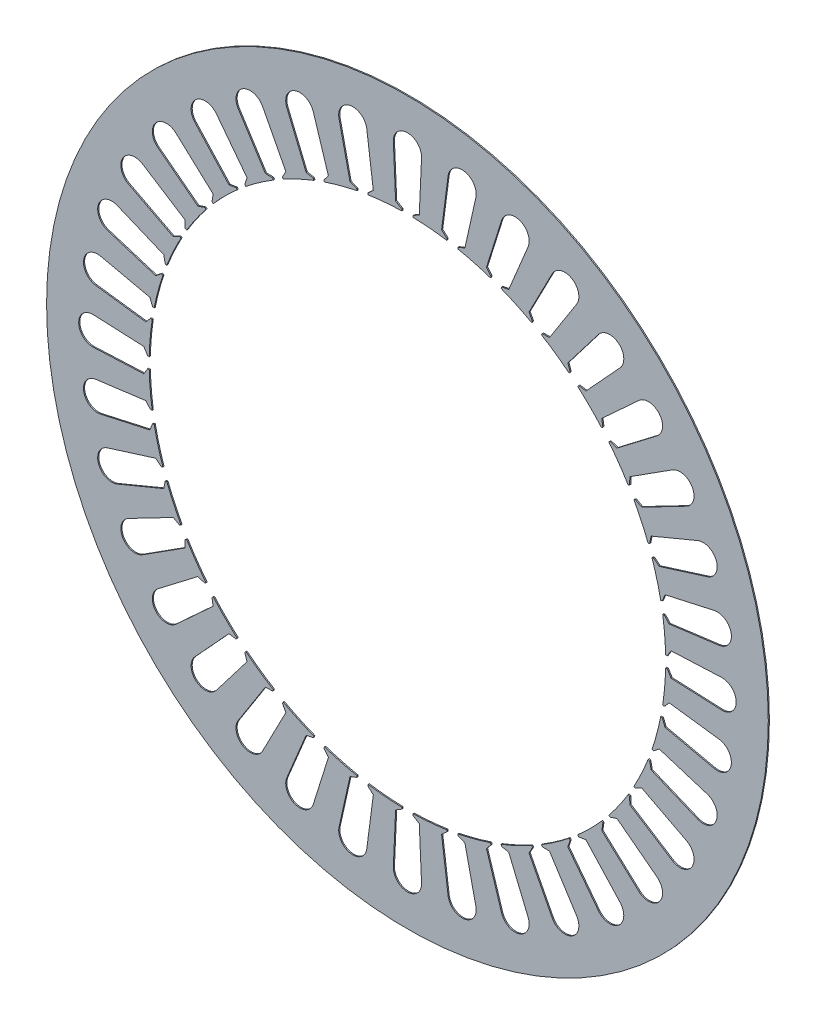
SolidWorks part; units mm, degrees
material "M19 Silicon Steel (29 Gauge)"
ref_plane "Front Plane" through (0, 0, 0) normal (0, 0, 1) x (1, 0, 0)
ref_plane "Top Plane" through (0, 0, 0) normal (0, 1, 0) x (1, 0, 0)
ref_plane "Right Plane" through (0, 0, 0) normal (1, 0, 0) x (0, 0, -1)
sketch "Stator sketch" plane through (0, 0, 0) normal (0, 0, 1) x (1, 0, 0)
  line L0 (0, 0) -> (0, 64) construction
  line L1 (2.0989, 46.7539) -> (2.5, 55.6878)
  line L2 (-2.0989, 46.7539) -> (-2.5, 55.6878)
  line L5 (-1.0066, 46.0891) -> (-2.0989, 46.7539)
  line L6 (-1, 45.7891) -> (-1.0066, 46.0891)
  line L7 (1.0066, 46.0891) -> (2.0989, 46.7539)
  line L8 (1, 45.7891) -> (1.0066, 46.0891)
  line L9 (6.9664, 45.2671) -> (7.012, 45.5637)
  line L10 (7.012, 45.5637) -> (6.0517, 46.4081)
  line L11 (6.0517, 46.4081) -> (7.2081, 55.2759)
  line L12 (8.936, 44.9198) -> (8.9945, 45.2141)
  line L13 (8.9945, 45.2141) -> (10.1858, 45.6791)
  line L14 (10.1858, 45.6791) -> (12.1321, 54.4076)
  line L15 (14.7211, 43.3697) -> (14.8175, 43.6538)
  line L16 (14.8175, 43.6538) -> (14.0184, 44.6522)
  line L17 (14.0184, 44.6522) -> (16.6971, 53.1844)
  line L18 (16.6005, 42.6856) -> (16.7092, 42.9653)
  line L19 (16.7092, 42.9653) -> (17.9631, 43.2164)
  line L20 (17.9631, 43.2164) -> (21.3956, 51.4743)
  line L21 (22.0285, 40.1545) -> (22.1728, 40.4176)
  line L22 (22.1728, 40.4176) -> (21.5592, 41.5395)
  line L23 (21.5592, 41.5395) -> (25.6788, 49.477)
  line L24 (23.7606, 39.1545) -> (23.9162, 39.411)
  line L25 (23.9162, 39.411) -> (25.1947, 39.4406)
  line L26 (25.1947, 39.4406) -> (30.0089, 46.977)
  line L27 (28.6666, 35.7193) -> (28.8544, 35.9533)
  line L28 (28.8544, 35.9533) -> (28.445, 37.1647)
  line L29 (28.445, 37.1647) -> (33.8803, 44.2663)
  line L30 (30.1987, 34.4337) -> (30.3966, 34.6593)
  line L31 (30.3966, 34.6593) -> (31.6607, 34.4664)
  line L32 (31.6607, 34.4664) -> (37.7105, 41.0523)
  line L33 (34.4337, 30.1987) -> (34.6593, 30.3966)
  line L34 (34.6593, 30.3966) -> (34.4664, 31.6607)
  line L35 (34.4664, 31.6607) -> (41.0523, 37.7105)
  line L36 (35.7193, 28.6666) -> (35.9533, 28.8544)
  line L37 (35.9533, 28.8544) -> (37.1647, 28.445)
  line L38 (37.1647, 28.445) -> (44.2663, 33.8803)
  line L39 (39.1545, 23.7606) -> (39.411, 23.9162)
  line L40 (39.411, 23.9162) -> (39.4406, 25.1947)
  line L41 (39.4406, 25.1947) -> (46.977, 30.0089)
  line L42 (40.1545, 22.0285) -> (40.4176, 22.1728)
  line L43 (40.4176, 22.1728) -> (41.5395, 21.5592)
  line L44 (41.5395, 21.5592) -> (49.477, 25.6788)
  line L45 (42.6856, 16.6005) -> (42.9653, 16.7092)
  line L46 (42.9653, 16.7092) -> (43.2164, 17.9631)
  line L47 (43.2164, 17.9631) -> (51.4743, 21.3956)
  line L48 (43.3697, 14.7211) -> (43.6538, 14.8175)
  line L49 (43.6538, 14.8175) -> (44.6522, 14.0184)
  line L50 (44.6522, 14.0184) -> (53.1844, 16.6971)
  line L51 (44.9198, 8.936) -> (45.2141, 8.9945)
  line L52 (45.2141, 8.9945) -> (45.6791, 10.1858)
  line L53 (45.6791, 10.1858) -> (54.4076, 12.1321)
  line L54 (45.2671, 6.9664) -> (45.5637, 7.012)
  line L55 (45.5637, 7.012) -> (46.4081, 6.0517)
  line L56 (46.4081, 6.0517) -> (55.2759, 7.2081)
  line L57 (45.7891, 1) -> (46.0891, 1.0066)
  line L58 (46.0891, 1.0066) -> (46.7539, 2.0989)
  line L59 (46.7539, 2.0989) -> (55.6878, 2.5)
  line L60 (45.7891, -1) -> (46.0891, -1.0066)
  line L61 (46.0891, -1.0066) -> (46.7539, -2.0989)
  line L62 (46.7539, -2.0989) -> (55.6878, -2.5)
  line L63 (45.2671, -6.9664) -> (45.5637, -7.012)
  line L64 (45.5637, -7.012) -> (46.4081, -6.0517)
  line L65 (46.4081, -6.0517) -> (55.2759, -7.2081)
  line L66 (44.9198, -8.936) -> (45.2141, -8.9945)
  line L67 (45.2141, -8.9945) -> (45.6791, -10.1858)
  line L68 (45.6791, -10.1858) -> (54.4076, -12.1321)
  line L69 (43.3697, -14.7211) -> (43.6538, -14.8175)
  line L70 (43.6538, -14.8175) -> (44.6522, -14.0184)
  line L71 (44.6522, -14.0184) -> (53.1844, -16.6971)
  line L72 (42.6856, -16.6005) -> (42.9653, -16.7092)
  line L73 (42.9653, -16.7092) -> (43.2164, -17.9631)
  line L74 (43.2164, -17.9631) -> (51.4743, -21.3956)
  line L75 (40.1545, -22.0285) -> (40.4176, -22.1728)
  line L76 (40.4176, -22.1728) -> (41.5395, -21.5592)
  line L77 (41.5395, -21.5592) -> (49.477, -25.6788)
  line L78 (39.1545, -23.7606) -> (39.411, -23.9162)
  line L79 (39.411, -23.9162) -> (39.4406, -25.1947)
  line L80 (39.4406, -25.1947) -> (46.977, -30.0089)
  line L81 (35.7193, -28.6666) -> (35.9533, -28.8544)
  line L82 (35.9533, -28.8544) -> (37.1647, -28.445)
  line L83 (37.1647, -28.445) -> (44.2663, -33.8803)
  line L84 (34.4337, -30.1987) -> (34.6593, -30.3966)
  line L85 (34.6593, -30.3966) -> (34.4664, -31.6607)
  line L86 (34.4664, -31.6607) -> (41.0523, -37.7105)
  line L87 (30.1987, -34.4337) -> (30.3966, -34.6593)
  line L88 (30.3966, -34.6593) -> (31.6607, -34.4664)
  line L89 (31.6607, -34.4664) -> (37.7105, -41.0523)
  line L90 (28.6666, -35.7193) -> (28.8544, -35.9533)
  line L91 (28.8544, -35.9533) -> (28.445, -37.1647)
  line L92 (28.445, -37.1647) -> (33.8803, -44.2663)
  line L93 (23.7606, -39.1545) -> (23.9162, -39.411)
  line L94 (23.9162, -39.411) -> (25.1947, -39.4406)
  line L95 (25.1947, -39.4406) -> (30.0089, -46.977)
  line L96 (22.0285, -40.1545) -> (22.1728, -40.4176)
  line L97 (22.1728, -40.4176) -> (21.5592, -41.5395)
  line L98 (21.5592, -41.5395) -> (25.6788, -49.477)
  line L99 (16.6005, -42.6856) -> (16.7092, -42.9653)
  line L100 (16.7092, -42.9653) -> (17.9631, -43.2164)
  line L101 (17.9631, -43.2164) -> (21.3956, -51.4743)
  line L102 (14.7211, -43.3697) -> (14.8175, -43.6538)
  line L103 (14.8175, -43.6538) -> (14.0184, -44.6522)
  line L104 (14.0184, -44.6522) -> (16.6971, -53.1844)
  line L105 (8.936, -44.9198) -> (8.9945, -45.2141)
  line L106 (8.9945, -45.2141) -> (10.1858, -45.6791)
  line L107 (10.1858, -45.6791) -> (12.1321, -54.4076)
  line L108 (6.9664, -45.2671) -> (7.012, -45.5637)
  line L109 (7.012, -45.5637) -> (6.0517, -46.4081)
  line L110 (6.0517, -46.4081) -> (7.2081, -55.2759)
  line L111 (1, -45.7891) -> (1.0066, -46.0891)
  line L112 (1.0066, -46.0891) -> (2.0989, -46.7539)
  line L113 (2.0989, -46.7539) -> (2.5, -55.6878)
  line L114 (-1, -45.7891) -> (-1.0066, -46.0891)
  line L115 (-1.0066, -46.0891) -> (-2.0989, -46.7539)
  line L116 (-2.0989, -46.7539) -> (-2.5, -55.6878)
  line L117 (-6.9664, -45.2671) -> (-7.012, -45.5637)
  line L118 (-7.012, -45.5637) -> (-6.0517, -46.4081)
  line L119 (-6.0517, -46.4081) -> (-7.2081, -55.2759)
  line L120 (-8.936, -44.9198) -> (-8.9945, -45.2141)
  line L121 (-8.9945, -45.2141) -> (-10.1858, -45.6791)
  line L122 (-10.1858, -45.6791) -> (-12.1321, -54.4076)
  line L123 (-14.7211, -43.3697) -> (-14.8175, -43.6538)
  line L124 (-14.8175, -43.6538) -> (-14.0184, -44.6522)
  line L125 (-14.0184, -44.6522) -> (-16.6971, -53.1844)
  line L126 (-16.6005, -42.6856) -> (-16.7092, -42.9653)
  line L127 (-16.7092, -42.9653) -> (-17.9631, -43.2164)
  line L128 (-17.9631, -43.2164) -> (-21.3956, -51.4743)
  line L129 (-22.0285, -40.1545) -> (-22.1728, -40.4176)
  line L130 (-22.1728, -40.4176) -> (-21.5592, -41.5395)
  line L131 (-21.5592, -41.5395) -> (-25.6788, -49.477)
  line L132 (-23.7606, -39.1545) -> (-23.9162, -39.411)
  line L133 (-23.9162, -39.411) -> (-25.1947, -39.4406)
  line L134 (-25.1947, -39.4406) -> (-30.0089, -46.977)
  line L135 (-28.6666, -35.7193) -> (-28.8544, -35.9533)
  line L136 (-28.8544, -35.9533) -> (-28.445, -37.1647)
  line L137 (-28.445, -37.1647) -> (-33.8803, -44.2663)
  line L138 (-30.1987, -34.4337) -> (-30.3966, -34.6593)
  line L139 (-30.3966, -34.6593) -> (-31.6607, -34.4664)
  line L140 (-31.6607, -34.4664) -> (-37.7105, -41.0523)
  line L141 (-34.4337, -30.1987) -> (-34.6593, -30.3966)
  line L142 (-34.6593, -30.3966) -> (-34.4664, -31.6607)
  line L143 (-34.4664, -31.6607) -> (-41.0523, -37.7105)
  line L144 (-35.7193, -28.6666) -> (-35.9533, -28.8544)
  line L145 (-35.9533, -28.8544) -> (-37.1647, -28.445)
  line L146 (-37.1647, -28.445) -> (-44.2663, -33.8803)
  line L147 (-39.1545, -23.7606) -> (-39.411, -23.9162)
  line L148 (-39.411, -23.9162) -> (-39.4406, -25.1947)
  line L149 (-39.4406, -25.1947) -> (-46.977, -30.0089)
  line L150 (-40.1545, -22.0285) -> (-40.4176, -22.1728)
  line L151 (-40.4176, -22.1728) -> (-41.5395, -21.5592)
  line L152 (-41.5395, -21.5592) -> (-49.477, -25.6788)
  line L153 (-42.6856, -16.6005) -> (-42.9653, -16.7092)
  line L154 (-42.9653, -16.7092) -> (-43.2164, -17.9631)
  line L155 (-43.2164, -17.9631) -> (-51.4743, -21.3956)
  line L156 (-43.3697, -14.7211) -> (-43.6538, -14.8175)
  line L157 (-43.6538, -14.8175) -> (-44.6522, -14.0184)
  line L158 (-44.6522, -14.0184) -> (-53.1844, -16.6971)
  line L159 (-44.9198, -8.936) -> (-45.2141, -8.9945)
  line L160 (-45.2141, -8.9945) -> (-45.6791, -10.1858)
  line L161 (-45.6791, -10.1858) -> (-54.4076, -12.1321)
  line L162 (-45.2671, -6.9664) -> (-45.5637, -7.012)
  line L163 (-45.5637, -7.012) -> (-46.4081, -6.0517)
  line L164 (-46.4081, -6.0517) -> (-55.2759, -7.2081)
  line L165 (-45.7891, -1) -> (-46.0891, -1.0066)
  line L166 (-46.0891, -1.0066) -> (-46.7539, -2.0989)
  line L167 (-46.7539, -2.0989) -> (-55.6878, -2.5)
  line L168 (-45.7891, 1) -> (-46.0891, 1.0066)
  line L169 (-46.0891, 1.0066) -> (-46.7539, 2.0989)
  line L170 (-46.7539, 2.0989) -> (-55.6878, 2.5)
  line L171 (-45.2671, 6.9664) -> (-45.5637, 7.012)
  line L172 (-45.5637, 7.012) -> (-46.4081, 6.0517)
  line L173 (-46.4081, 6.0517) -> (-55.2759, 7.2081)
  line L174 (-44.9198, 8.936) -> (-45.2141, 8.9945)
  line L175 (-45.2141, 8.9945) -> (-45.6791, 10.1858)
  line L176 (-45.6791, 10.1858) -> (-54.4076, 12.1321)
  line L177 (-43.3697, 14.7211) -> (-43.6538, 14.8175)
  line L178 (-43.6538, 14.8175) -> (-44.6522, 14.0184)
  line L179 (-44.6522, 14.0184) -> (-53.1844, 16.6971)
  line L180 (-42.6856, 16.6005) -> (-42.9653, 16.7092)
  line L181 (-42.9653, 16.7092) -> (-43.2164, 17.9631)
  line L182 (-43.2164, 17.9631) -> (-51.4743, 21.3956)
  line L183 (-40.1545, 22.0285) -> (-40.4176, 22.1728)
  line L184 (-40.4176, 22.1728) -> (-41.5395, 21.5592)
  line L185 (-41.5395, 21.5592) -> (-49.477, 25.6788)
  line L186 (-39.1545, 23.7606) -> (-39.411, 23.9162)
  line L187 (-39.411, 23.9162) -> (-39.4406, 25.1947)
  line L188 (-39.4406, 25.1947) -> (-46.977, 30.0089)
  line L189 (-35.7193, 28.6666) -> (-35.9533, 28.8544)
  line L190 (-35.9533, 28.8544) -> (-37.1647, 28.445)
  line L191 (-37.1647, 28.445) -> (-44.2663, 33.8803)
  line L192 (-34.4337, 30.1987) -> (-34.6593, 30.3966)
  line L193 (-34.6593, 30.3966) -> (-34.4664, 31.6607)
  line L194 (-34.4664, 31.6607) -> (-41.0523, 37.7105)
  line L195 (-30.1987, 34.4337) -> (-30.3966, 34.6593)
  line L196 (-30.3966, 34.6593) -> (-31.6607, 34.4664)
  line L197 (-31.6607, 34.4664) -> (-37.7105, 41.0523)
  line L198 (-28.6666, 35.7193) -> (-28.8544, 35.9533)
  line L199 (-28.8544, 35.9533) -> (-28.445, 37.1647)
  line L200 (-28.445, 37.1647) -> (-33.8803, 44.2663)
  line L201 (-23.7606, 39.1545) -> (-23.9162, 39.411)
  line L202 (-23.9162, 39.411) -> (-25.1947, 39.4406)
  line L203 (-25.1947, 39.4406) -> (-30.0089, 46.977)
  line L204 (-22.0285, 40.1545) -> (-22.1728, 40.4176)
  line L205 (-22.1728, 40.4176) -> (-21.5592, 41.5395)
  line L206 (-21.5592, 41.5395) -> (-25.6788, 49.477)
  line L207 (-16.6005, 42.6856) -> (-16.7092, 42.9653)
  line L208 (-16.7092, 42.9653) -> (-17.9631, 43.2164)
  line L209 (-17.9631, 43.2164) -> (-21.3956, 51.4743)
  line L210 (-14.7211, 43.3697) -> (-14.8175, 43.6538)
  line L211 (-14.8175, 43.6538) -> (-14.0184, 44.6522)
  line L212 (-14.0184, 44.6522) -> (-16.6971, 53.1844)
  line L213 (-8.936, 44.9198) -> (-8.9945, 45.2141)
  line L214 (-8.9945, 45.2141) -> (-10.1858, 45.6791)
  line L215 (-10.1858, 45.6791) -> (-12.1321, 54.4076)
  line L216 (-6.9664, 45.2671) -> (-7.012, 45.5637)
  line L217 (-7.012, 45.5637) -> (-6.0517, 46.4081)
  line L218 (-6.0517, 46.4081) -> (-7.2081, 55.2759)
  arc A0 (-1, 45.7891) -> (-6.9664, 45.2671) centre (0, 0) ccw
  circle A1 centre (0, 0) radius 64
  arc A2 (-2.5, 55.6878) -> (2.5, 55.6878) centre (0, 55.8) cw
  arc A3 (7.2081, 55.2759) -> (12.1321, 54.4076) centre (9.6896, 54.9523) cw
  arc A4 (16.6971, 53.1844) -> (21.3956, 51.4743) centre (19.0847, 52.4348) cw
  arc A5 (25.6788, 49.477) -> (30.0089, 46.977) centre (27.9, 48.3242) cw
  arc A6 (33.8803, 44.2663) -> (37.7105, 41.0523) centre (35.8675, 42.7453) cw
  arc A7 (41.0523, 37.7105) -> (44.2663, 33.8803) centre (42.7453, 35.8675) cw
  arc A8 (46.977, 30.0089) -> (49.477, 25.6788) centre (48.3242, 27.9) cw
  arc A9 (51.4743, 21.3956) -> (53.1844, 16.6971) centre (52.4348, 19.0847) cw
  arc A10 (54.4076, 12.1321) -> (55.2759, 7.2081) centre (54.9523, 9.6896) cw
  arc A11 (55.6878, 2.5) -> (55.6878, -2.5) centre (55.8, 0) cw
  arc A12 (55.2759, -7.2081) -> (54.4076, -12.1321) centre (54.9523, -9.6896) cw
  arc A13 (53.1844, -16.6971) -> (51.4743, -21.3956) centre (52.4348, -19.0847) cw
  arc A14 (49.477, -25.6788) -> (46.977, -30.0089) centre (48.3242, -27.9) cw
  arc A15 (44.2663, -33.8803) -> (41.0523, -37.7105) centre (42.7453, -35.8675) cw
  arc A16 (37.7105, -41.0523) -> (33.8803, -44.2663) centre (35.8675, -42.7453) cw
  arc A17 (30.0089, -46.977) -> (25.6788, -49.477) centre (27.9, -48.3242) cw
  arc A18 (21.3956, -51.4743) -> (16.6971, -53.1844) centre (19.0847, -52.4348) cw
  arc A19 (12.1321, -54.4076) -> (7.2081, -55.2759) centre (9.6896, -54.9523) cw
  arc A20 (2.5, -55.6878) -> (-2.5, -55.6878) centre (0, -55.8) cw
  arc A21 (-7.2081, -55.2759) -> (-12.1321, -54.4076) centre (-9.6896, -54.9523) cw
  arc A22 (-16.6971, -53.1844) -> (-21.3956, -51.4743) centre (-19.0847, -52.4348) cw
  arc A23 (-25.6788, -49.477) -> (-30.0089, -46.977) centre (-27.9, -48.3242) cw
  arc A24 (-33.8803, -44.2663) -> (-37.7105, -41.0523) centre (-35.8675, -42.7453) cw
  arc A25 (-41.0523, -37.7105) -> (-44.2663, -33.8803) centre (-42.7453, -35.8675) cw
  arc A26 (-46.977, -30.0089) -> (-49.477, -25.6788) centre (-48.3242, -27.9) cw
  arc A27 (-51.4743, -21.3956) -> (-53.1844, -16.6971) centre (-52.4348, -19.0847) cw
  arc A28 (-54.4076, -12.1321) -> (-55.2759, -7.2081) centre (-54.9523, -9.6896) cw
  arc A29 (-55.6878, -2.5) -> (-55.6878, 2.5) centre (-55.8, 0) cw
  arc A30 (-55.2759, 7.2081) -> (-54.4076, 12.1321) centre (-54.9523, 9.6896) cw
  arc A31 (-53.1844, 16.6971) -> (-51.4743, 21.3956) centre (-52.4348, 19.0847) cw
  arc A32 (-49.477, 25.6788) -> (-46.977, 30.0089) centre (-48.3242, 27.9) cw
  arc A33 (-44.2663, 33.8803) -> (-41.0523, 37.7105) centre (-42.7453, 35.8675) cw
  arc A34 (-37.7105, 41.0523) -> (-33.8803, 44.2663) centre (-35.8675, 42.7453) cw
  arc A35 (-30.0089, 46.977) -> (-25.6788, 49.477) centre (-27.9, 48.3242) cw
  arc A36 (-21.3956, 51.4743) -> (-16.6971, 53.1844) centre (-19.0847, 52.4348) cw
  arc A37 (-12.1321, 54.4076) -> (-7.2081, 55.2759) centre (-9.6896, 54.9523) cw
  arc A38 (-8.936, 44.9198) -> (-14.7211, 43.3697) centre (0, 0) ccw
  arc A39 (-16.6005, 42.6856) -> (-22.0285, 40.1545) centre (0, 0) ccw
  arc A40 (-23.7606, 39.1545) -> (-28.6666, 35.7193) centre (0, 0) ccw
  arc A41 (-30.1987, 34.4337) -> (-34.4337, 30.1987) centre (0, 0) ccw
  arc A42 (-35.7193, 28.6666) -> (-39.1545, 23.7606) centre (0, 0) ccw
  arc A43 (-40.1545, 22.0285) -> (-42.6856, 16.6005) centre (0, 0) ccw
  arc A44 (-43.3697, 14.7211) -> (-44.9198, 8.936) centre (0, 0) ccw
  arc A45 (-45.2671, 6.9664) -> (-45.7891, 1) centre (0, 0) ccw
  arc A46 (-45.7891, -1) -> (-45.2671, -6.9664) centre (0, 0) ccw
  arc A47 (-44.9198, -8.936) -> (-43.3697, -14.7211) centre (0, 0) ccw
  arc A48 (-42.6856, -16.6005) -> (-40.1545, -22.0285) centre (0, 0) ccw
  arc A49 (-39.1545, -23.7606) -> (-35.7193, -28.6666) centre (0, 0) ccw
  arc A50 (-34.4337, -30.1987) -> (-30.1987, -34.4337) centre (0, 0) ccw
  arc A51 (-28.6666, -35.7193) -> (-23.7606, -39.1545) centre (0, 0) ccw
  arc A52 (-22.0285, -40.1545) -> (-16.6005, -42.6856) centre (0, 0) ccw
  arc A53 (-14.7211, -43.3697) -> (-8.936, -44.9198) centre (0, 0) ccw
  arc A54 (-6.9664, -45.2671) -> (-1, -45.7891) centre (0, 0) ccw
  arc A55 (1, -45.7891) -> (6.9664, -45.2671) centre (0, 0) ccw
  arc A56 (8.936, -44.9198) -> (14.7211, -43.3697) centre (0, 0) ccw
  arc A57 (16.6005, -42.6856) -> (22.0285, -40.1545) centre (0, 0) ccw
  arc A58 (23.7606, -39.1545) -> (28.6666, -35.7193) centre (0, 0) ccw
  arc A59 (30.1987, -34.4337) -> (34.4337, -30.1987) centre (0, 0) ccw
  arc A60 (35.7193, -28.6666) -> (39.1545, -23.7606) centre (0, 0) ccw
  arc A61 (40.1545, -22.0285) -> (42.6856, -16.6005) centre (0, 0) ccw
  arc A62 (43.3697, -14.7211) -> (44.9198, -8.936) centre (0, 0) ccw
  arc A63 (45.2671, -6.9664) -> (45.7891, -1) centre (0, 0) ccw
  arc A64 (45.7891, 1) -> (45.2671, 6.9664) centre (0, 0) ccw
  arc A65 (44.9198, 8.936) -> (43.3697, 14.7211) centre (0, 0) ccw
  arc A66 (42.6856, 16.6005) -> (40.1545, 22.0285) centre (0, 0) ccw
  arc A67 (39.1545, 23.7606) -> (35.7193, 28.6666) centre (0, 0) ccw
  arc A68 (34.4337, 30.1987) -> (30.1987, 34.4337) centre (0, 0) ccw
  arc A69 (28.6666, 35.7193) -> (23.7606, 39.1545) centre (0, 0) ccw
  arc A70 (22.0285, 40.1545) -> (16.6005, 42.6856) centre (0, 0) ccw
  arc A71 (14.7211, 43.3697) -> (8.936, 44.9198) centre (0, 0) ccw
  arc A72 (6.9664, 45.2671) -> (1, 45.7891) centre (0, 0) ccw
  point P1 (-2.054, 45.7539)
  point P9 (-1, 45.7891)
  point P13 (0, 45.8)
  point P15 (1, 45.7891)
  point P335 (0, 0)
  dimension "D1" = 91.6
  dimension "D2" = 128
  dimension "D3" = 5
  dimension "D4" = 10
  dimension "D5" = 2
  dimension "D6" = 1
  dimension "D7" = 0.3
  dimension "D8" = 36
extrude "Boss-Extrude1" add sketch "Stator sketch" along normal mid plane 0.2
equation "\"Inner diameter\"= 91.6mm"
equation "\"Slots\"= 36"
equation "\"Stator OD\"= 128mm"
equation "\"Slot width\"= 5mm"
equation "\"Slot depth\"= 10mm"
equation "\"Slot opening\"= 2mm"
equation "\"D1@Stator sketch\"=\"Inner diameter\""
equation "\"D2@Stator sketch\"=\"Stator OD\""
equation "\"D3@Stator sketch\"=\"Slot width\""
equation "\"D4@Stator sketch\"=\"Slot depth\""
equation "\"D5@Stator sketch\"=\"Slot opening\""
equation "\"Lamination thickness\"= 0.2mm"
equation "\"D1@Boss-Extrude1\"=\"Lamination thickness\""
